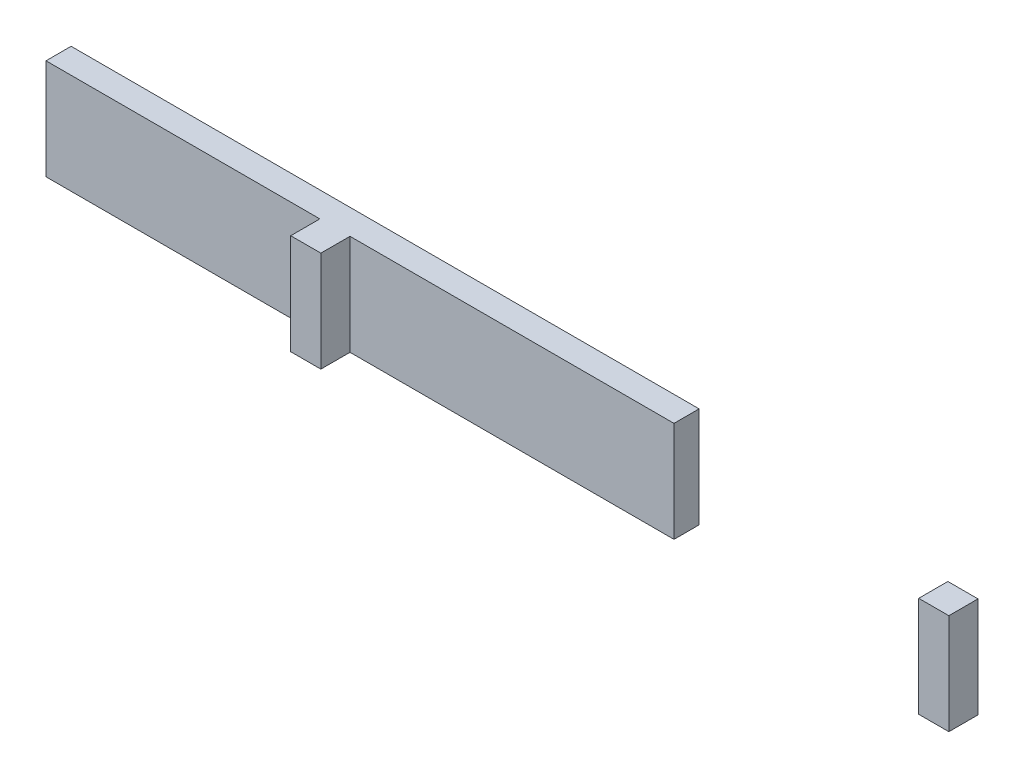
SolidWorks part; units mm, degrees
ref_plane "Plan de face" through (0, 0, 0) normal (0, 0, 1) x (1, 0, 0)
ref_plane "Plan de dessus" through (0, 0, 0) normal (0, 1, 0) x (1, 0, 0)
ref_plane "Plan de droite" through (0, 0, 0) normal (1, 0, 0) x (0, 0, -1)
sketch "Esquisse1" plane through (0, 0, 0) normal (0, 0, 1) x (1, 0, 0)
  line L1 (0, 0) -> (250, 0)
  line L2 (0, 0) -> (0, 40)
  line L3 (0, 40) -> (250, 40)
  line L4 (250, 0) -> (250, 40)
  dimension "D1" = 40
  dimension "D2" = 250
extrude "Boss.-Extru.1" add sketch "Esquisse1" along normal blind 10
sketch "Esquisse2" plane through (0, 0, 10) normal (0, 0, 1) x (1, 0, 0)
  line L0 (250, 40) -> (0, 40) construction
  line L1 (109.02, 40) -> (121.02, 40)
  line L2 (109.02, 40) -> (109.02, 0)
  line L3 (109.02, 0) -> (121.02, 0)
  line L4 (121.02, 40) -> (121.02, 0)
  line L5 (0, 0) -> (250, 0) construction
  line L7 (359.02, 40) -> (371.02, 40)
  line L8 (359.02, 40) -> (359.02, 0)
  line L9 (359.02, 0) -> (371.02, 0)
  line L10 (371.02, 40) -> (371.02, 0)
  dimension "D1" = 12
  dimension "D2" = 109.02
  dimension "D3" = 250
extrude "Boss.-Extru.2" add sketch "Esquisse2" along normal blind 11.6
